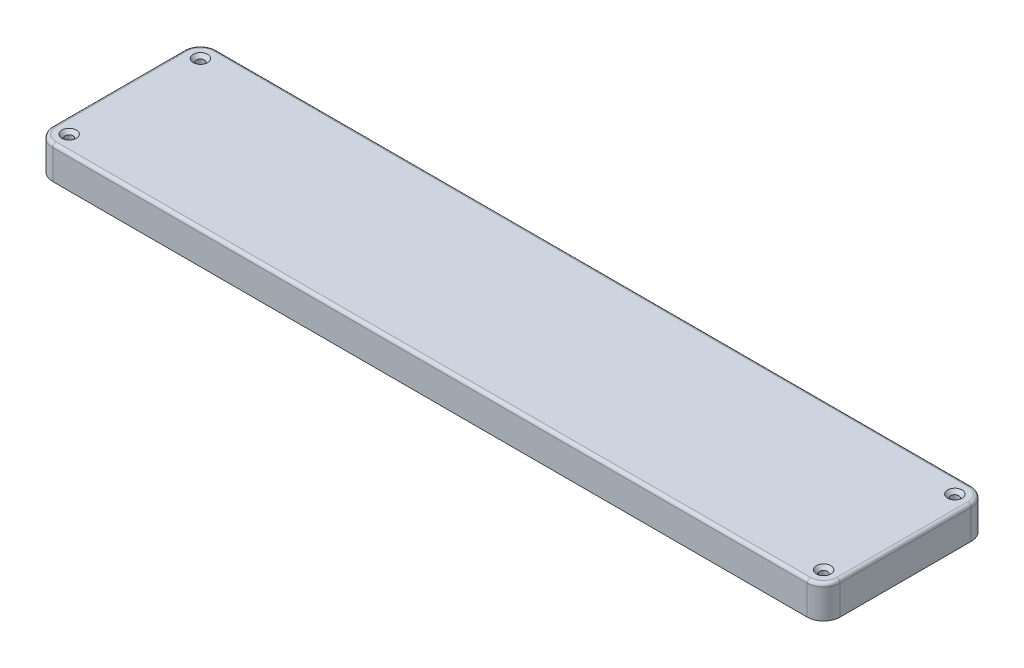
SolidWorks part; units mm, degrees
ref_plane "Front Plane" through (0, 0, 0) normal (0, 0, 1) x (1, 0, 0)
ref_plane "Top Plane" through (0, 0, 0) normal (0, 1, 0) x (1, 0, 0)
ref_plane "Right Plane" through (0, 0, 0) normal (1, 0, 0) x (0, 0, -1)
sketch "Sketch1" plane through (0, 0, 0) normal (0, 1, 0) x (1, 0, 0)
  line L0 (-115, 25) -> (115, 25)
  line L5 (-120, 20) -> (-120, -20)
  line L6 (-115, -25) -> (115, -25)
  line L7 (120, 20) -> (120, -20)
  line L8 (-120, 25) -> (120, -25) construction
  line L9 (-120, -25) -> (120, 25) construction
  arc A0 (115, 25) -> (120, 20) centre (115, 20) cw
  arc A1 (115, -25) -> (120, -20) centre (115, -20) ccw
  arc A2 (-120, -20) -> (-115, -25) centre (-115, -20) ccw
  arc A3 (-115, 25) -> (-120, 20) centre (-115, 20) ccw
  point P0 (0, 0)
  point P18 (0, 0)
  dimension "D3" = 5
  dimension "D1" = 240
  dimension "D2" = 50
extrude "Boss-Extrude1" add sketch "Sketch1" against normal blind 10
sketch "Sketch2" plane through (0, -10, 0) normal (0, -1, 0) x (1, 0, 0)
  line L0 (109.6449, 21.9834) -> (-109.6449, 21.9834)
  line L1 (-116.9457, 14.7251) -> (-116.9457, -14.7251)
  line L2 (-109.6449, -21.9834) -> (109.6449, -21.9834)
  line L3 (116.9457, -14.7251) -> (116.9457, 14.7251)
  line L4 (115.0116, 24.9834) -> (-114.9364, 24.9834)
  line L5 (-119.9127, 19.997) -> (-119.9457, -20.0124)
  line L6 (-114.9364, -25.0166) -> (115.0116, -25.0166)
  line L7 (120.0543, -20.1813) -> (120.0872, 19.7855)
  line L8 (0, 0) -> (0, -10.1808) construction
  line L9 (0, 0) -> (4.464, 0) construction
  line L10 (120, 20) -> (120, -20) construction
  line L11 (-115, 25) -> (115, 25) construction
  arc A0 (-114.9364, 24.9834) -> (-119.9127, 19.997) centre (-114.9262, 19.997) ccw
  arc A1 (-119.9457, -20.0124) -> (-114.9364, -25.0166) centre (-114.9457, -20.0166) ccw
  arc A2 (120.0872, 19.7855) -> (115.0116, 24.9834) centre (115.0016, 19.8966) ccw
  arc A3 (115.0116, -25.0166) -> (120.0543, -20.1813) centre (114.9947, -19.9518) ccw
  arc A4 (120.0872, 19.7855) -> (115.0116, 24.9834) centre (115.0016, 19.8966) ccw
  arc A5 (-114.9364, 24.9834) -> (-119.9127, 19.997) centre (-114.9262, 19.997) ccw
  arc A6 (-119.9457, -20.0124) -> (-114.9364, -25.0166) centre (-114.9457, -20.0166) ccw
  arc A7 (115.0116, -25.0166) -> (120.0543, -20.1813) centre (114.9947, -19.9518) ccw
  arc A8 (-109.6449, 21.9834) -> (-110.1262, 21.348) centre (-109.6449, 21.4834) ccw
  arc A9 (-116.3072, 15.2055) -> (-116.9457, 14.7251) centre (-116.4457, 14.7251) ccw
  arc A10 (115.979, 14.9045) -> (116.9457, 14.7251) centre (116.4457, 14.7251) cw
  arc A11 (109.6449, 21.9834) -> (110.1259, 21.3471) centre (109.6449, 21.4834) cw
  arc A12 (116.0232, -14.9926) -> (116.9457, -14.7251) centre (116.4457, -14.7251) ccw
  arc A13 (109.6449, -21.9834) -> (110.1259, -21.3471) centre (109.6449, -21.4834) ccw
  arc A14 (-109.6449, -21.9834) -> (-110.1259, -21.3471) centre (-109.6449, -21.4834) cw
  arc A15 (-116.3093, -15.2061) -> (-116.9457, -14.7251) centre (-116.4457, -14.7251) cw
  arc A16 (-116.3072, 15.2055) -> (-110.1262, 21.348) centre (-114.9262, 19.997) ccw
  arc A17 (-110.1259, -21.3471) -> (-116.3093, -15.2061) centre (-114.9457, -20.0166) ccw
  arc A18 (116.0232, -14.9926) -> (110.1259, -21.3471) centre (114.9947, -19.9518) ccw
  arc A19 (110.1259, 21.3471) -> (115.979, 14.9045) centre (115.0016, 19.8966) ccw
  point P39 (0, 0)
  point P40 (0, 0)
  point P42 (7.0947, 7.4383)
  point P47 (0, 0)
  point P48 (0, 0)
  point P49 (0, 0)
  dimension "D1" = 1
  dimension "D2" = 1
  dimension "D3" = 50
  dimension "240" = 240
  dimension "D4" = 3
extrude "Cut-Extrude1" cut sketch "Sketch2" against normal blind 7 contours A19 A11 L0 A8 A16 A9 L1 A15 A17 A14 L2 A13 A18 A12 L3 A10
sketch "Sketch3" plane through (0, 0, 0) normal (0, 1, 0) x (1, 0, 0)
  line L1 (115, -20) -> (-115, -20) construction
  line L2 (115, -20) -> (115, 20) construction
  line L3 (115, 20) -> (-115, 20) construction
  line L4 (-115, -20) -> (-115, 20) construction
  line L5 (115, -20) -> (-115, 20) construction
  line L6 (115, 20) -> (-115, -20) construction
  point P0 (0, 0)
hole_wizard "CSK for M2 Countersunk Flat Head Screw2" positions "3DSketch1" profile "Sketch5" countersink size "M2" standard "ISO" end condition through all
sketch3d "3DSketch1"
  point P0 (-115, 0, -20)
  point P3 (-115, 0, 20)
  point P6 (115, 0, -20)
  point P9 (115, 0, 20)
sketch "Sketch5" plane through (-115, 0, -20) normal (1, 0, 0) x (0, 0, 1)
  line L0 (0, 0) -> (0, 10)
  line L1 (0, 10) -> (1.2, 10)
  line L2 (1.2, 10) -> (1.2, 1)
  line L3 (1.2, 1) -> (2.2, 0)
  line L5 (2.2, 0) -> (0, 0)
  line L6 (-1.2, 1) -> (-2.2, 0) construction
  line L11 (0, -6.35) -> (0, 107.95) construction
  dimension "Thru Hole Dia." = 2.4
  dimension "Thru Hole Depth" = 10
  dimension "Near C'Sink Dia." = 4.4
  dimension "Near C'Sink Angle" = 90
fillet "Fillet1" radius 1 8 edges at (-118.5355, 0, 23.5355) (-120, 0, 0) (-118.5355, 0, -23.5355) (0, 0, -25) (118.5355, 0, -23.5355) (120, 0, 0) (118.5355, 0, 23.5355) (0, 0, 25)
